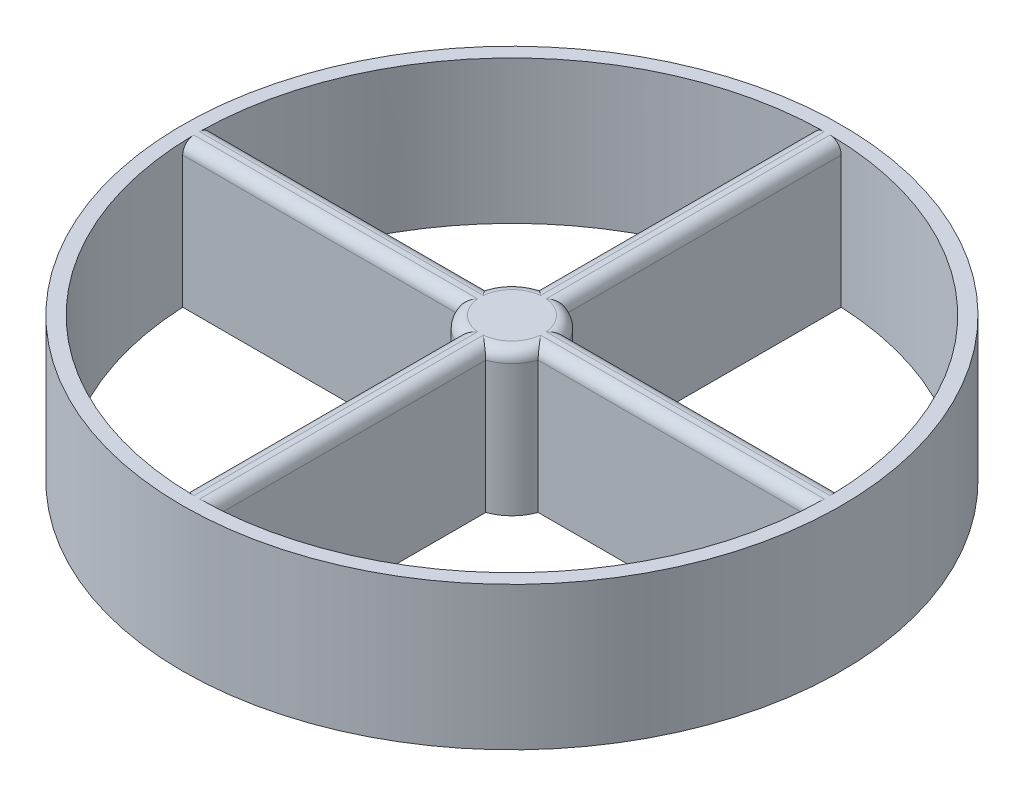
SolidWorks part; units mm, degrees
ref_plane "Front Plane" through (0, 0, 0) normal (0, 0, 1) x (1, 0, 0)
ref_plane "Top Plane" through (0, 0, 0) normal (0, 1, 0) x (1, 0, 0)
ref_plane "Right Plane" through (0, 0, 0) normal (1, 0, 0) x (0, 0, -1)
sketch "Sketch1" plane through (0, 0, 0) normal (0, 1, 0) x (1, 0, 0)
  line L2 (-1, 21.9773) -> (-1, 2.8284)
  line L3 (1, 21.9773) -> (1, 2.8284)
  line L4 (-21.9773, -1) -> (-2.8284, -1)
  line L5 (-21.9773, 1) -> (-2.8284, 1)
  line L6 (2.8284, 1) -> (21.9773, 1)
  line L8 (-1, -2.8284) -> (-1, -21.9773)
  line L13 (1, -2.8284) -> (1, -21.9773)
  line L15 (2.8284, -1) -> (21.9773, -1)
  circle A0 centre (0, 0) radius 23
  arc A1 (-21.9773, -1) -> (-1, -21.9773) centre (0, 0) ccw
  arc A2 (-1, 21.9773) -> (-21.9773, 1) centre (0, 0) ccw
  arc A3 (21.9773, 1) -> (1, 21.9773) centre (0, 0) ccw
  arc A4 (1, -21.9773) -> (21.9773, -1) centre (0, 0) ccw
  arc A5 (-1, 2.8284) -> (-2.8284, 1) centre (0, 0) ccw
  arc A6 (-2.8284, -1) -> (-1, -2.8284) centre (0, 0) ccw
  arc A7 (2.8284, 1) -> (1, 2.8284) centre (0, 0) ccw
  arc A8 (1, -2.8284) -> (2.8284, -1) centre (0, 0) ccw
  dimension "D1" = 46
  dimension "D2" = 22
  dimension "D3" = 1
  dimension "D4" = 6
  dimension "D5" = 2
  dimension "D6" = 2
  dimension "D7" = 1
  dimension "D8" = 1
extrude "Boss-Extrude1" add sketch "Sketch1" along normal blind 10
fillet "Fillet1" radius 0.8 12 edges at (-12.4028, 10, -1) (-1, 10, -12.4028) (1, 10, -12.4028) (-2.1213, 10, -2.1213) (-2.1213, 10, 2.1213) (2.1213, 10, 2.1213) (2.1213, 10, -2.1213) (12.4028, 10, -1) (12.4028, 10, 1) (1, 10, 12.4028) (-1, 10, 12.4028) (-12.4028, 10, 1)
sketch "Sketch2" plane through (0, 0, 0) normal (0, -1, 0) x (1, 0, 0)
  circle A0 centre (0, 0) radius 1.5
  dimension "D1" = 3
extrude "Cut-Extrude1" cut sketch "Sketch2" against normal blind 6
